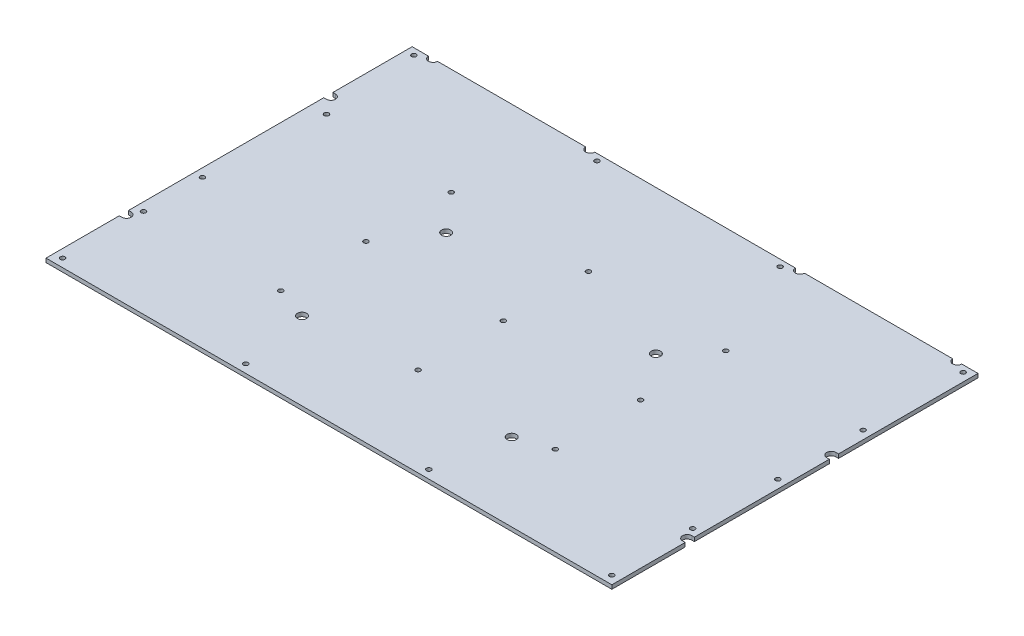
SolidWorks part; units mm, degrees
ref_plane "Front Plane" through (0, 0, 0) normal (0, 0, 1) x (1, 0, 0)
ref_plane "Top Plane" through (0, 0, 0) normal (0, 1, 0) x (1, 0, 0)
ref_plane "Right Plane" through (0, 0, 0) normal (1, 0, 0) x (0, 0, -1)
sketch "Sketch1" plane through (0, 0, 0) normal (0, 1, 0) x (1, 0, 0)
  line L1 (-215.9, -147.35) -> (215.9, -147.35)
  line L2 (-215.9, -147.35) -> (-215.9, 147.35)
  line L3 (-215.9, 147.35) -> (215.9, 147.35)
  line L4 (215.9, -147.35) -> (215.9, 147.35)
  line L5 (-215.9, -147.35) -> (215.9, 147.35) construction
  line L6 (-215.9, 147.35) -> (215.9, -147.35) construction
  point P0 (0, 0)
  dimension "D1" = 294.7
  dimension "D2" = 431.8
extrude "Boss-Extrude1" add sketch "Sketch1" along normal blind 3
sketch "Sketch2" plane through (0, 3, 0) normal (0, 1, 0) x (1, 0, 0)
  line L0 (-215.9, 147.35) -> (-215.9, -147.35) construction
  line L1 (-215.9, -147.35) -> (215.9, -147.35) construction
  line L2 (215.9, 147.35) -> (-215.9, 147.35) construction
  circle A0 centre (-209.55, -125.7) radius 1.775
  circle A1 centre (-209.55, 142.35) radius 1.775
  dimension "D3" = 3.55
  dimension "D5" = 6.35
  dimension "D6" = 3.55
  dimension "D1" = 6.35
  dimension "D2" = 21.65
  dimension "D4" = 5
extrude "Cut-Extrude1" cut sketch "Sketch2" against normal through all
pattern_linear "LPattern1" count 4 spacing 139.7 along (1, 0, 0) of "Cut-Extrude1"
sketch "Sketch3" plane through (0, 3, 0) normal (0, 1, 0) x (1, 0, 0)
  line L0 (-209.55, -64) -> (-209.55, -125.7) construction
  line L1 (215.9, 147.35) -> (-215.9, 147.35) construction
  circle A0 centre (-209.55, -64) radius 1.775
  dimension "D2" = 3.55
  dimension "D1" = 211.35
extrude "Cut-Extrude2" cut sketch "Sketch3" against normal through all
pattern_linear "LPattern2" count 5 spacing 104.77 along (1, 0, 0) count 3 spacing 65 along (0, 0, -1) skipping (0, 1), (0, 2) of "Cut-Extrude2"
sketch "Sketch4" plane through (0, 3, 0) normal (0, 1, 0) x (1, 0, 0)
  line L0 (-209.55, -19) -> (-209.55, -64) construction
  line L1 (-215.9, 147.35) -> (-215.9, -147.35) construction
  circle A0 centre (-203.9, 70) radius 1.775
  circle A2 centre (-104.78, 66) radius 1.775 construction
  circle A3 centre (-209.55, -64) radius 1.775 construction
  circle A4 centre (-209.55, -19) radius 1.775
  dimension "D1" = 4
  dimension "D2" = 45
  dimension "D3" = 12
extrude "Cut-Extrude3" cut sketch "Sketch4" against normal blind 10
sketch "Sketch7" plane through (0, 0, 0) normal (0, -1, 0) x (1, 0, 0)
  circle A0 centre (-213.9, -83.38) radius 3.5
  circle A1 centre (-213.9, 72.58) radius 3.5
  circle A2 centre (-200, 140.04) radius 3.5 construction
  circle A3 centre (-80, 140.04) radius 3.5 construction
  circle A4 centre (80, 140.04) radius 3.5 construction
  circle A5 centre (200, 140.04) radius 3.5 construction
  circle A6 centre (213.9, 72.58) radius 3.5
  circle A7 centre (213.9, -37.42) radius 3.5
  circle A8 centre (200, -147.42) radius 3.5
  circle A9 centre (80, -147.42) radius 3.5
  circle A10 centre (-80, -147.42) radius 3.5
  circle A11 centre (-80, -37.42) radius 3.5
  circle A12 centre (80, -37.42) radius 3.5
  circle A13 centre (80, 72.58) radius 3.5
  circle A14 centre (-80, 72.58) radius 3.5
  circle A15 centre (-200, -147.42) radius 3.5
  dimension "D1" = 7
extrude "Cut-Extrude5" cut sketch "Sketch7" against normal through all
sketch "Sketch8" plane through (0, 3, 0) normal (0, 1, 0) x (1, 0, 0)
  line L0 (215.9, 40.2923) -> (215.9, 147.35) construction
  line L1 (213.9, 33.92) -> (215.9, 33.92)
  line L2 (213.9, 33.92) -> (213.9, 40.92)
  line L3 (213.9, 40.92) -> (215.9, 40.92)
  line L4 (215.9, 33.92) -> (215.9, 40.92)
  line L5 (215.9, -69.7077) -> (215.9, 34.5477) construction
  line L6 (213.9, -69.08) -> (215.9, -69.08)
  line L7 (213.9, -69.08) -> (213.9, -76.08)
  line L8 (213.9, -76.08) -> (215.9, -76.08)
  line L9 (215.9, -69.08) -> (215.9, -76.08)
  line L10 (-215.9, 80.5077) -> (-215.9, -69.7077) construction
  line L11 (-213.9, 86.88) -> (-215.9, 86.88)
  line L12 (-213.9, 86.88) -> (-213.9, 79.88)
  line L13 (-213.9, 79.88) -> (-215.9, 79.88)
  line L14 (-215.9, 86.88) -> (-215.9, 79.88)
  line L15 (-215.9, -75.4523) -> (-215.9, -147.35) construction
  line L16 (-213.9, -69.08) -> (-215.9, -69.08)
  line L17 (-213.9, -69.08) -> (-213.9, -76.08)
  line L18 (-213.9, -76.08) -> (-215.9, -76.08)
  line L19 (-215.9, -69.08) -> (-215.9, -76.08)
  arc A0 (215.9, 40.2923) -> (215.9, 34.5477) centre (213.9, 37.42) ccw construction
  arc A1 (215.9, -69.7077) -> (215.9, -75.4523) centre (213.9, -72.58) ccw construction
  arc A2 (-215.9, 80.5077) -> (-215.9, 86.2523) centre (-213.9, 83.38) ccw construction
  arc A3 (-215.9, -75.4523) -> (-215.9, -69.7077) centre (-213.9, -72.58) ccw construction
extrude "Cut-Extrude6" cut sketch "Sketch8" against normal through all
sketch "Sketch9" plane through (0, 0, 0) normal (0, -1, 0) x (1, 0, 0)
  line L0 (-215.9, 76.08) -> (-215.9, 147.35) construction
  line L1 (215.9, 147.35) -> (-215.9, 147.35)
  line L2 (215.9, 147.35) -> (215.9, 132.05)
  line L3 (215.9, 132.05) -> (-215.9, 132.05)
  line L4 (-215.9, 147.35) -> (-215.9, 132.05)
  dimension "D1" = 15.3
extrude "Cut-Extrude7" cut sketch "Sketch9" against normal through all
